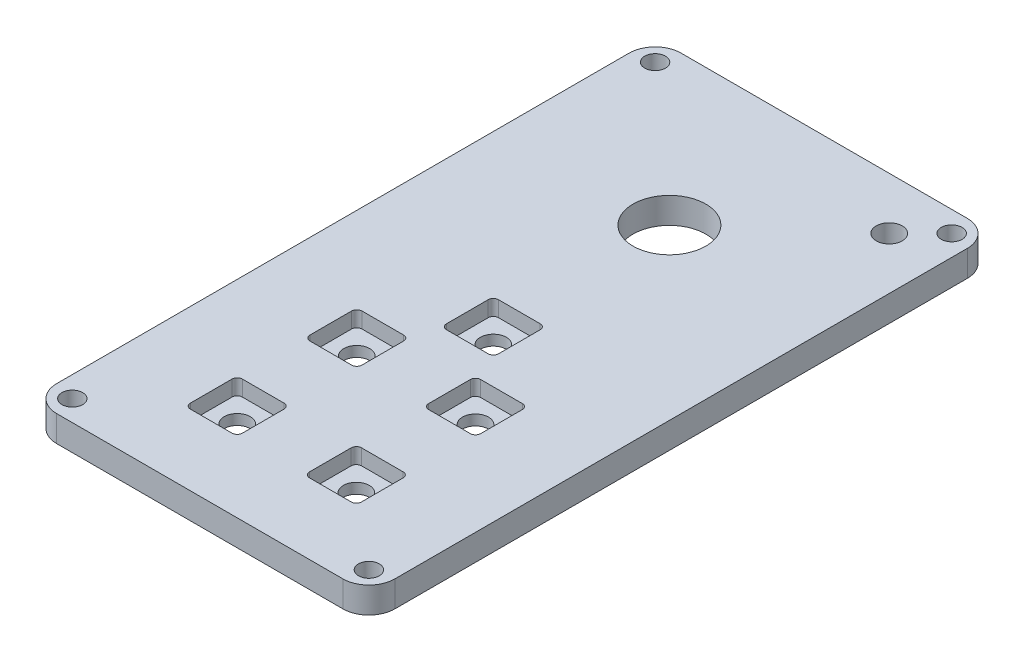
SolidWorks part; units mm, degrees
ref_plane "Front Plane" through (0, 0, 0) normal (0, 0, 1) x (1, 0, 0)
ref_plane "Top Plane" through (0, 0, 0) normal (0, 1, 0) x (1, 0, 0)
ref_plane "Right Plane" through (0, 0, 0) normal (1, 0, 0) x (0, 0, -1)
sketch "Sketch1" plane through (0, 0, 0) normal (0, 1, 0) x (1, 0, 0)
  line L1 (-27.5, 60) -> (27.5, 60)
  line L2 (-32.5, 55) -> (-32.5, -55)
  line L3 (-27.5, -60) -> (27.5, -60)
  line L4 (32.5, 55) -> (32.5, -55)
  line L5 (-32.5, 60) -> (32.5, -60) construction
  line L6 (-32.5, -60) -> (32.5, 60) construction
  arc A0 (-32.5, -55) -> (-27.5, -60) centre (-27.5, -55) ccw
  arc A1 (27.5, -60) -> (32.5, -55) centre (27.5, -55) ccw
  arc A2 (27.5, 60) -> (32.5, 55) centre (27.5, 55) cw
  arc A3 (-27.5, 60) -> (-32.5, 55) centre (-27.5, 55) ccw
  point P0 (0, 0)
  dimension "D3" = 5
  dimension "D1" = 65
  dimension "D2" = 120
extrude "Boss-Extrude1" add sketch "Sketch1" along normal blind 5
sketch "Sketch2" plane through (0, 5, 0) normal (0, 1, 0) x (1, 0, 0)
  line L0 (27.5, 60) -> (-27.5, 60) construction
  line L1 (-32.5, 55) -> (-32.5, -55) construction
  line L2 (32.5, -55) -> (32.5, 55) construction
  line L3 (-27.5, -60) -> (27.5, -60) construction
  circle A0 centre (-28.5, 56) radius 1.05
  circle A1 centre (28.5, 56) radius 1.05
  circle A2 centre (28.5, -56) radius 1.05
  circle A3 centre (-28.5, -56) radius 1.05
  dimension "D9" = 2.1
  dimension "D10" = 2.1
  dimension "D11" = 2.1
  dimension "D12" = 2.1
  dimension "D1" = 4
  dimension "D2" = 4
  dimension "D3" = 4
  dimension "D4" = 4
  dimension "D5" = 4
  dimension "D6" = 4
  dimension "D7" = 4
  dimension "D8" = 4
extrude "Cut-Extrude1" cut sketch "Sketch2" against normal up to surface (5 mm away) up to face at (0, 0, 0)
sketch "Sketch3" plane through (0, 5, 0) normal (0, 1, 0) x (1, 0, 0)
  circle A0 centre (-28.5, 56) radius 2
  circle A1 centre (28.5, 56) radius 2
  circle A2 centre (28.5, -56) radius 2
  circle A3 centre (-28.5, -56) radius 2
extrude "Cut-Extrude2" cut sketch "Sketch3" against normal blind 3
sketch "Sketch4" plane through (0, 5, 0) normal (0, 1, 0) x (1, 0, 0)
  line L0 (0, 60) -> (0, -60) construction
  line L1 (27.5, 60) -> (-27.5, 60) construction
  line L2 (-27.5, -60) -> (27.5, -60) construction
  line L3 (0, 60) -> (0, 48.7543)
  line L4 (-32.5, 55) -> (-32.5, -55) construction
  line L5 (-32.5, 0) -> (32.5, 0) construction
  line L6 (32.5, -55) -> (32.5, 55) construction
  line L7 (0, 48.7543) -> (0, 11.7543)
  circle A0 centre (0, 30.2543) radius 7
  dimension "D1" = 14
extrude "Cut-Extrude3" cut sketch "Sketch4" against normal through all contours L7 A0 | L7 A0
sketch "Sketch5" plane through (0, 5, 0) normal (0, 1, 0) x (1, 0, 0)
  line L0 (0, 0) -> (0, -4.7349) construction
  line L3 (32.5, -55) -> (32.5, 55) construction
  line L7 (27.5, 60) -> (-27.5, 60) construction
  circle A0 centre (22.5, 50) radius 2.5
  circle A1 centre (0, -3.5845) radius 2.5
  circle A2 centre (11.5681, -18.5845) radius 2.5
  circle A3 centre (11.4875, -41.4025) radius 2.5
  circle A4 centre (-11.4068, -41.4068) radius 2.5
  circle A5 centre (-11.2456, -18.5845) radius 2.5
  point P18 (0, -30)
  point P21 (0, -30)
  point P29 (0, 0)
  dimension "D1" = 15
  dimension "D2" = 10
  dimension "D3" = 10
extrude "Cut-Extrude5" cut sketch "Sketch5" against normal through all
sketch "Sketch6" plane through (0, 5, 0) normal (0, 1, 0) x (1, 0, 0)
  line L0 (0, 0) -> (0, -60) construction
  line L1 (-27.5, -60) -> (27.5, -60) construction
  line L3 (32.5, -55) -> (32.5, 55) construction
  line L4 (32.5, -30) -> (-32.5, -30) construction
  line L5 (-32.5, 55) -> (-32.5, -55) construction
  line L6 (7.5681, -13.5845) -> (15.5681, -13.5845)
  line L7 (6.5681, -14.5845) -> (6.5681, -22.5845)
  line L8 (7.5681, -23.5845) -> (15.5681, -23.5845)
  line L9 (16.5681, -14.5845) -> (16.5681, -22.5845)
  line L10 (6.5681, -13.5845) -> (16.5681, -23.5845) construction
  line L11 (6.5681, -23.5845) -> (16.5681, -13.5845) construction
  line L12 (-15.2456, -13.5845) -> (-7.2456, -13.5845)
  line L13 (-16.2456, -14.5845) -> (-16.2456, -22.5845)
  line L14 (-15.2456, -23.5845) -> (-7.2456, -23.5845)
  line L15 (-6.2456, -14.5845) -> (-6.2456, -22.5845)
  line L16 (-16.2456, -13.5845) -> (-6.2456, -23.5845) construction
  line L17 (-16.2456, -23.5845) -> (-6.2456, -13.5845) construction
  line L18 (-15.4068, -36.4068) -> (-7.4068, -36.4068)
  line L19 (-16.4068, -37.4068) -> (-16.4068, -45.4068)
  line L20 (-15.4068, -46.4068) -> (-7.4068, -46.4068)
  line L21 (-6.4068, -37.4068) -> (-6.4068, -45.4068)
  line L22 (-16.4068, -36.4068) -> (-6.4068, -46.4068) construction
  line L23 (-16.4068, -46.4068) -> (-6.4068, -36.4068) construction
  line L24 (7.4875, -36.4025) -> (15.4875, -36.4025)
  line L25 (6.4875, -37.4025) -> (6.4875, -45.4025)
  line L26 (7.4875, -46.4025) -> (15.4875, -46.4025)
  line L27 (16.4875, -37.4025) -> (16.4875, -45.4025)
  line L28 (6.4875, -36.4025) -> (16.4875, -46.4025) construction
  line L29 (6.4875, -46.4025) -> (16.4875, -36.4025) construction
  line L30 (-4, 1.4155) -> (4, 1.4155)
  line L31 (-5, 0.4155) -> (-5, -7.5845)
  line L32 (-4, -8.5845) -> (4, -8.5845)
  line L33 (5, 0.4155) -> (5, -7.5845)
  line L34 (-5, 1.4155) -> (5, -8.5845) construction
  line L35 (-5, -8.5845) -> (5, 1.4155) construction
  arc A0 (7.5681, -13.5845) -> (6.5681, -14.5845) centre (7.5681, -14.5845) ccw
  arc A1 (15.5681, -13.5845) -> (16.5681, -14.5845) centre (15.5681, -14.5845) cw
  arc A2 (15.5681, -23.5845) -> (16.5681, -22.5845) centre (15.5681, -22.5845) ccw
  arc A3 (6.5681, -22.5845) -> (7.5681, -23.5845) centre (7.5681, -22.5845) ccw
  arc A4 (7.4875, -36.4025) -> (6.4875, -37.4025) centre (7.4875, -37.4025) ccw
  arc A5 (15.4875, -36.4025) -> (16.4875, -37.4025) centre (15.4875, -37.4025) cw
  arc A6 (15.4875, -46.4025) -> (16.4875, -45.4025) centre (15.4875, -45.4025) ccw
  arc A7 (6.4875, -45.4025) -> (7.4875, -46.4025) centre (7.4875, -45.4025) ccw
  arc A8 (-16.4068, -45.4068) -> (-15.4068, -46.4068) centre (-15.4068, -45.4068) ccw
  arc A9 (-7.4068, -46.4068) -> (-6.4068, -45.4068) centre (-7.4068, -45.4068) ccw
  arc A10 (-7.4068, -36.4068) -> (-6.4068, -37.4068) centre (-7.4068, -37.4068) cw
  arc A11 (-15.4068, -36.4068) -> (-16.4068, -37.4068) centre (-15.4068, -37.4068) ccw
  arc A12 (-16.2456, -22.5845) -> (-15.2456, -23.5845) centre (-15.2456, -22.5845) ccw
  arc A13 (-7.2456, -23.5845) -> (-6.2456, -22.5845) centre (-7.2456, -22.5845) ccw
  arc A14 (-5, -7.5845) -> (-4, -8.5845) centre (-4, -7.5845) ccw
  arc A15 (4, -8.5845) -> (5, -7.5845) centre (4, -7.5845) ccw
  arc A16 (4, 1.4155) -> (5, 0.4155) centre (4, 0.4155) cw
  arc A17 (-4, 1.4155) -> (-5, 0.4155) centre (-4, 0.4155) ccw
  arc A18 (-7.2456, -13.5845) -> (-6.2456, -14.5845) centre (-7.2456, -14.5845) cw
  arc A19 (-15.2456, -13.5845) -> (-16.2456, -14.5845) centre (-15.2456, -14.5845) ccw
  point P5 (11.5681, -18.5845)
  point P17 (-11.2456, -18.5845)
  point P23 (-11.4068, -41.4068)
  point P29 (11.4875, -41.4025)
  point P35 (0, -3.5845)
  dimension "D11" = 1
  dimension "D1" = 10
  dimension "D2" = 10
  dimension "D3" = 10
  dimension "D4" = 10
  dimension "D5" = 10
  dimension "D6" = 10
  dimension "D7" = 10
  dimension "D8" = 10
  dimension "D9" = 10
  dimension "D10" = 10
extrude "Cut-Extrude7" cut sketch "Sketch6" against normal blind 3
